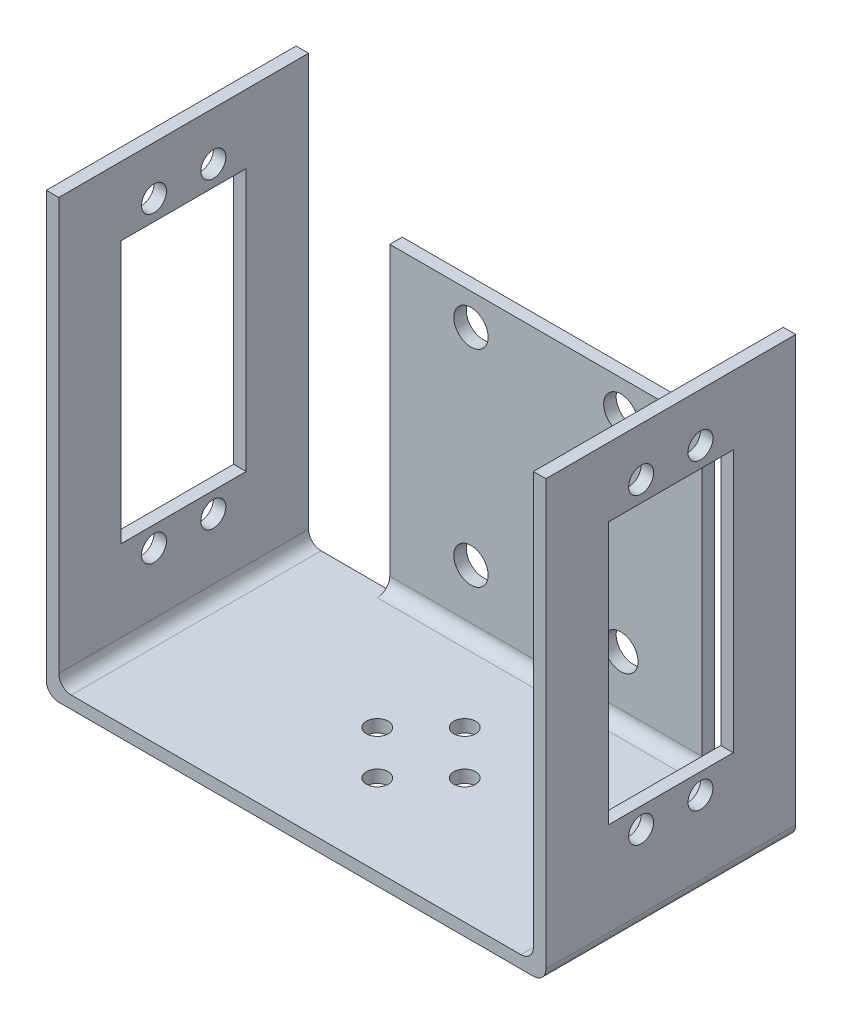
SolidWorks part; units mm, degrees
ref_plane "前视基准面" through (0, 0, 0) normal (0, 0, 1) x (1, 0, 0)
ref_plane "上视基准面" through (0, 0, 0) normal (0, 1, 0) x (1, 0, 0)
ref_plane "右视基准面" through (0, 0, 0) normal (1, 0, 0) x (0, 0, -1)
other "Configuration Table"
sketch "草图1" plane through (0, 0, 0) normal (0, 0, 1) x (1, 0, 0)
  line L0 (-38, 0) -> (38, 0)
  line L1 (38, 0) -> (38, 68)
  line L2 (38, 68) -> (40, 68)
  line L3 (40, 68) -> (40, -2)
  line L4 (40, -2) -> (-40, -2)
  line L5 (-40, -2) -> (-40, 68)
  line L6 (-40, 68) -> (-38, 68)
  line L7 (-38, 68) -> (-38, 0)
  dimension "D1" = 2
  dimension "D2" = 2
  dimension "D3" = 70
  dimension "D4" = 80
extrude "凸台-拉伸1" add sketch "草图1" along normal mid plane 40
sketch "草图2" plane through (0, 0, 0) normal (0, 1, 0) x (1, 0, 0)
  circle A0 centre (0, 0) radius 7 construction
  circle A1 centre (0, 7) radius 1.75
  circle A2 centre (-7, 0) radius 1.75
  circle A3 centre (0, -7) radius 1.75
  circle A4 centre (7, 0) radius 1.75
  dimension "D1" = 14
  dimension "D2" = 3.5
extrude "切除-拉伸1" cut sketch "草图2" against normal blind 10
sketch "草图3" plane through (40, 0, 0) normal (1, 0, 0) x (0, 0, -1)
  line L1 (-10, 57) -> (10, 57)
  line L2 (-10, 57) -> (-10, 15)
  line L3 (-10, 15) -> (10, 15)
  line L4 (10, 57) -> (10, 15)
  point P4 (0, 15)
  dimension "D1" = 15
  dimension "D2" = 42
  dimension "D3" = 20
extrude "切除-拉伸2" cut sketch "草图3" against normal through all
sketch "草图4" plane through (40, 0, 0) normal (1, 0, 0) x (0, 0, -1)
  line L0 (-20, -2) -> (20, -2) construction
  circle A0 centre (-4.75, 60.25) radius 2
  circle A1 centre (4.75, 60.25) radius 2
  circle A2 centre (-4.75, 11.75) radius 2
  circle A3 centre (4.75, 11.75) radius 2
  dimension "D1" = 9.5
  dimension "D4" = 4
  dimension "D5" = 4.75
  dimension "D6" = 4.75
  dimension "D2" = 48.5
  dimension "D3" = 13.75
extrude "切除-拉伸3" cut sketch "草图4" against normal through all
sketch "草图8" plane through (0, 0, 0) normal (1, 0, 0) x (0, 0, -1)
  line L0 (20, -2) -> (22, -2)
  line L1 (22, -2) -> (22, 48)
  line L5 (20, -2) -> (20, 68) construction
  line L6 (20, 48) -> (20, -2)
  line L7 (20, 48) -> (22, 48)
  dimension "D2" = 50
  dimension "D4" = 2
extrude "凸台-拉伸4" add sketch "草图8" along normal mid plane 50
sketch "草图9" plane through (0, 0, -20) normal (0, 0, 1) x (1, 0, 0)
  line L0 (25, 0) -> (-25, 0) construction
  line L1 (25, 48) -> (-25, 48) construction
  circle A0 centre (12, 10) radius 2.75
  circle A1 centre (12, 43) radius 2.75
  dimension "D1" = 12
  dimension "D3" = 5.5
  dimension "D4" = 10
  dimension "D5" = 5
  dimension "D2" = 12
extrude "切除-拉伸4" cut sketch "草图9" against normal blind 8
mirror "镜向1" about plane through (0, 0, 0) normal (1, 0, 0) of "切除-拉伸4"
fillet "圆角1" radius 2 6 edges at (0, -2, -22) (0, 0, -20) (-38, 0, 0) (-40, -2, 0) (40, -2, 0) (38, 0, 0)
